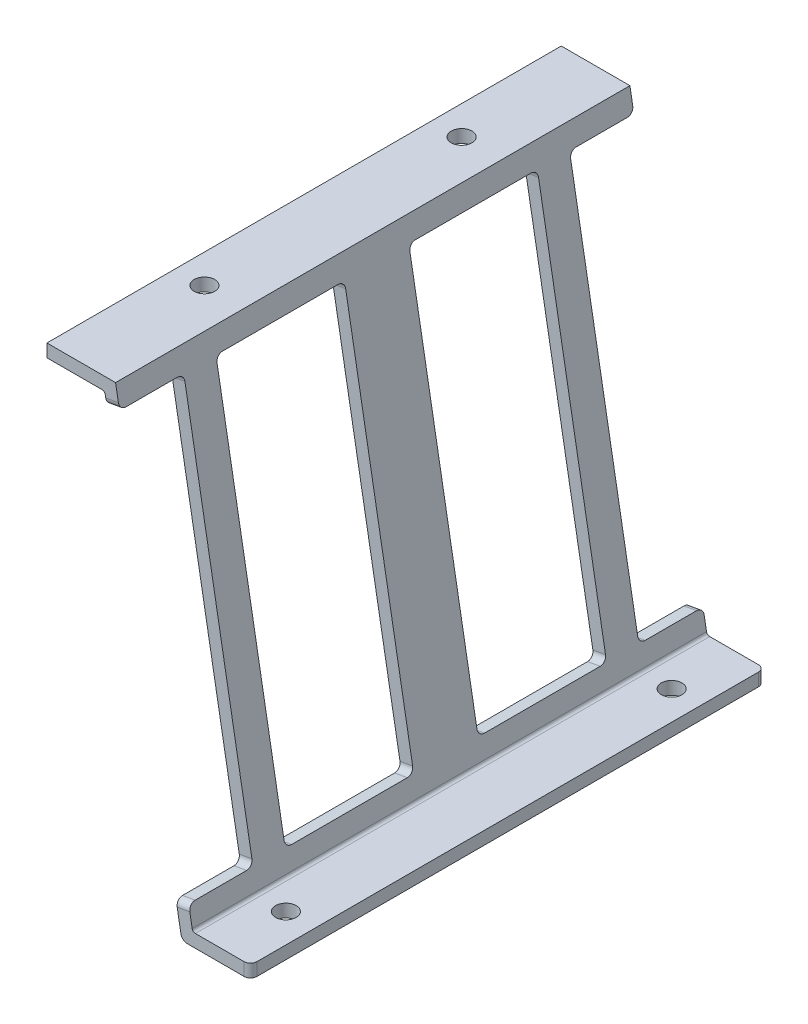
SolidWorks part; units mm, degrees
ref_plane "前视基准面" through (0, 0, 0) normal (0, 0, 1) x (1, 0, 0)
ref_plane "上视基准面" through (0, 0, 0) normal (0, 1, 0) x (1, 0, 0)
ref_plane "右视基准面" through (0, 0, 0) normal (1, 0, 0) x (0, 0, -1)
sketch "草图1" plane through (0, 0, 0) normal (0, 0, 1) x (1, 0, 0)
  line L0 (5.7944, 1.0853) -> (17.7847, -66.9147)
  line L1 (-4.8838, 1.0853) -> (5.7944, 1.0853)
  line L2 (-4.8838, 1.0853) -> (-4.8838, -0.9147)
  line L3 (-4.8838, -0.9147) -> (4.1162, -0.9147)
  line L5 (-4.8838, 1.0853) -> (4.1162, -0.9147) construction
  line L6 (-4.8838, -0.9147) -> (5.7944, 1.0853) construction
  line L7 (4.1162, -0.9147) -> (16.1065, -68.9147)
  line L9 (16.1065, -68.9147) -> (26.7847, -68.9147)
  line L10 (26.7847, -68.9147) -> (26.7847, -66.9147)
  line L11 (26.7847, -66.9147) -> (17.7847, -66.9147)
  point P0 (0, 0)
  dimension "D1" = 2
  dimension "D2" = 9
  dimension "D3" = 80
  dimension "D4" = 9
  dimension "D5" = 2
  dimension "D6" = 2
  dimension "D7" = 70
extrude "凸台-拉伸1" add sketch "草图1" along normal blind 80
sketch "草图2" plane through (0, 1.0853, 0) normal (0, 1, 0) x (1, 0, 0)
  line L0 (-5.2675, -40) -> (8.5755, -40) construction
  line L2 (-0.3838, 0) -> (-0.3838, -52.142) construction
  line L3 (-4.8838, 0) -> (4.1162, 0) construction
  line L4 (-4.8838, 0) -> (4.1162, 0) construction
  line L5 (-4.8838, -80) -> (-4.8838, 0) construction
  line L6 (-4.8838, -80) -> (-4.8838, 0) construction
  circle A0 centre (-0.3838, -20) radius 1.6
  circle A1 centre (-0.3838, -60) radius 1.6
  point P1 (0, 0)
  point P5 (-0.3838, 0)
  point P15 (-4.8838, -40)
  dimension "D1" = 3.2
  dimension "D2" = 20
extrude "切除-拉伸1" cut sketch "草图2" against normal blind 50
sketch "草图5" plane through (0, -66.9147, 0) normal (0, 1, 0) x (1, 0, 0)
  line L0 (26.7847, -40) -> (32.5723, -40) construction
  line L1 (26.7847, -80) -> (26.7847, 0) construction
  line L2 (22.2847, 0) -> (22.2847, -85.5959) construction
  line L3 (26.7847, 0) -> (17.7847, 0) construction
  circle A0 centre (22.2847, -10) radius 1.6
  circle A1 centre (22.2847, -70) radius 1.6
  dimension "D1" = 3.2
  dimension "D2" = 60
extrude "切除-拉伸2" cut sketch "草图5" against normal blind 50
sketch "草图9" plane through (5.8053, 1.0236, 0) normal (0.9848, 0.1736, 0) x (0, 0, -1)
  line L0 (-40, 0.0626) -> (-40, -68.9864) construction
  line L1 (-80, 0.0626) -> (0, 0.0626) construction
  line L2 (-80, -68.9864) -> (0, -68.9864) construction
  line L3 (-10, -65.4619) -> (-15, -65.4619)
  line L4 (-45, -3.4619) -> (-35, -3.4619)
  line L5 (-45, -3.4619) -> (-45, -65.4619)
  line L6 (-45, -65.4619) -> (-35, -65.4619)
  line L7 (-35, -3.4619) -> (-35, -65.4619)
  line L8 (-45, -3.4619) -> (-35, -65.4619) construction
  line L9 (-45, -65.4619) -> (-35, -3.4619) construction
  line L10 (-70, -3.4619) -> (-65, -3.4619)
  line L11 (-70, -3.4619) -> (-70, -65.4619)
  line L12 (-70, -65.4619) -> (-65, -65.4619)
  line L13 (-65, -3.4619) -> (-65, -65.4619)
  line L14 (-70, -3.4619) -> (-65, -65.4619) construction
  line L15 (-70, -65.4619) -> (-65, -3.4619) construction
  line L16 (-15, -3.4619) -> (-15, -65.4619)
  line L17 (-10, -3.4619) -> (-15, -3.4619)
  line L18 (-10, -3.4619) -> (-10, -65.4619)
  line L19 (-80, -68.9864) -> (-80, 0.0626) construction
  line L20 (-80, -3.4619) -> (-70, -3.4619)
  line L21 (-80, -3.4619) -> (-80, -65.4619)
  line L22 (-80, -65.4619) -> (-70, -65.4619)
  line L23 (-70, -3.4619) -> (-70, -65.4619)
  line L24 (0, -68.9864) -> (0, 0.0626) construction
  line L25 (-65, -3.4619) -> (-45, -3.4619)
  line L26 (-65, -3.4619) -> (-65, -65.4619)
  line L27 (-65, -65.4619) -> (-45, -65.4619)
  line L28 (-45, -3.4619) -> (-45, -65.4619)
  line L29 (-35, -3.4619) -> (-15, -3.4619)
  line L30 (-35, -3.4619) -> (-35, -65.4619)
  line L31 (-35, -65.4619) -> (-15, -65.4619)
  line L32 (-15, -3.4619) -> (-15, -65.4619)
  line L33 (-10, -3.4619) -> (0, -3.4619)
  line L34 (-10, -3.4619) -> (-10, -65.4619)
  line L35 (-10, -65.4619) -> (0, -65.4619)
  line L36 (0, -3.4619) -> (0, -65.4619)
  point P6 (-40, -34.4619)
  point P11 (-67.5, -34.4619)
  line M8 (0, -68.9864) -> (0, 0.0626)
  line M10 (-80, 0.0626) -> (-80, -68.9864)
  dimension "D1" = 10
  dimension "D2" = 62
  dimension "D3" = 5
  dimension "D4" = 20
extrude "切除-拉伸6" cut sketch "草图9" against normal blind 50 contours L22 L11 L20 M10 | L13 L27 L5 L25 | L7 L31 L16 L29 | L18 L35 L33 M8
fillet "圆角1" radius 1 1 edges at (16.1065, -68.9147, 40)
fillet "圆角2" radius 1 10 edges at (16.1878, -63.6174, 0) (16.1878, -63.6174, 80) (16.1878, -63.6174, 10) (16.1878, -63.6174, 15) (16.1878, -63.6174, 35) (16.1878, -63.6174, 70) (16.1878, -63.6174, 65) (16.1878, -63.6174, 45) (5.4216, -2.5593, 80) (5.4216, -2.5593, 0)
fillet "圆角3" radius 1 8 edges at (5.4216, -2.5593, 10) (5.4216, -2.5593, 15) (5.4216, -2.5593, 35) (5.4216, -2.5593, 45) (5.4216, -2.5593, 65) (5.4216, -2.5593, 70) (26.7847, -67.9147, 0) (26.7847, -67.9147, 80)
fillet "圆角4" radius 0.5 1 edges at (17.7847, -66.9147, 40)
fillet "圆角5" radius 0.5 1 edges at (4.1162, -0.9147, 40)
